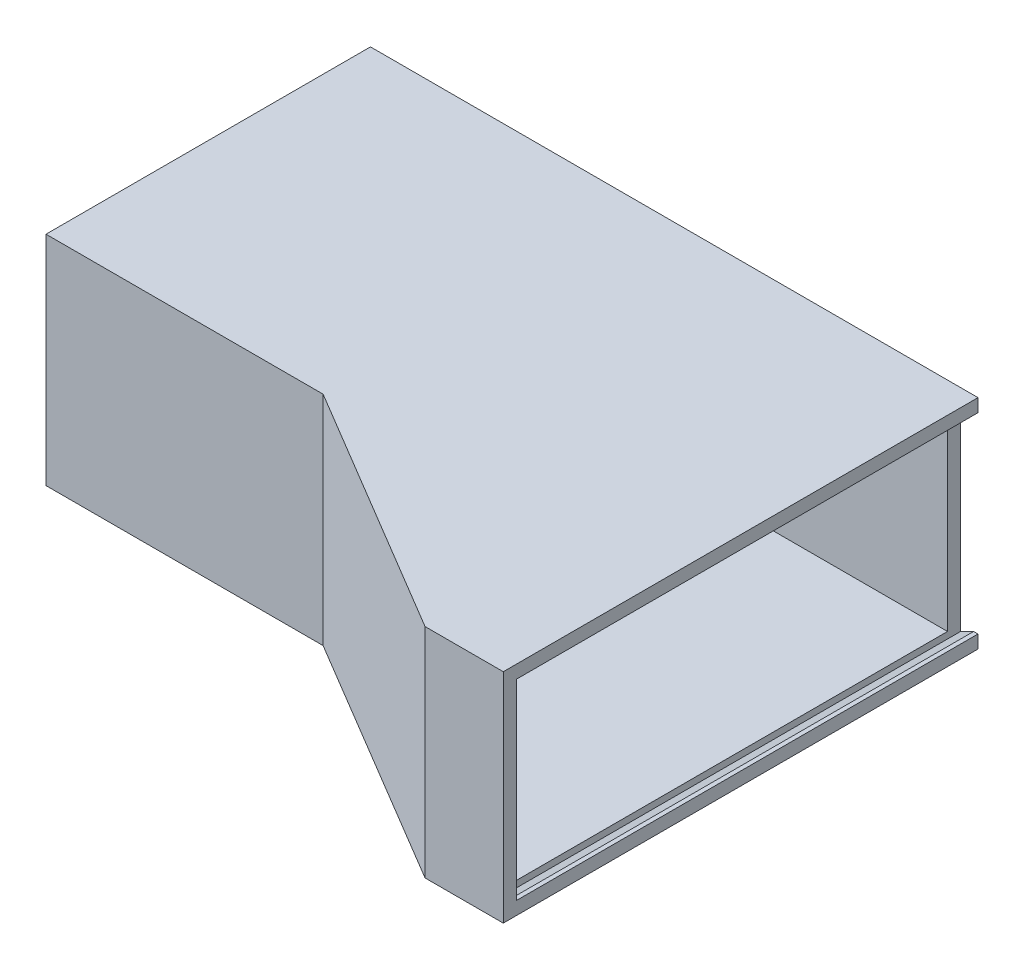
SolidWorks part; units mm, degrees
ref_plane "Front Plane" through (0, 0, 0) normal (0, 0, 1) x (1, 0, 0)
ref_plane "Top Plane" through (0, 0, 0) normal (0, 1, 0) x (1, 0, 0)
ref_plane "Right Plane" through (0, 0, 0) normal (1, 0, 0) x (0, 0, -1)
sketch "PCB" plane through (0, 0, 0) normal (0, 1, 0) x (1, 0, 0)
  line L0 (0, 0) -> (131.5, 0)
  line L1 (131.5, 0) -> (131.5, -102)
  line L2 (131.5, -102) -> (119, -102)
  line L3 (0, 0) -> (0, -67.5)
  line L4 (0, -67.5) -> (72, -67.5)
  line L5 (72, -67.5) -> (72, -74)
  line L6 (72, -74) -> (119, -102)
  line L7 (71.5, -74.2841) -> (118.8624, -102.5)
  line L8 (132, -102.5) -> (118.8624, -102.5)
  line L9 (132, 0.5) -> (132, -102.5)
  line L10 (-0.5, 0.5) -> (132, 0.5)
  line L11 (-0.5, 0.5) -> (-0.5, -68)
  line L12 (-0.5, -68) -> (71.5, -68)
  line L13 (71.5, -68) -> (71.5, -74.2841)
  line L14 (68.5, -75.9889) -> (118.0365, -105.5)
  line L15 (135, -105.5) -> (118.0365, -105.5)
  line L17 (-3.5, 3.5) -> (135, 3.5)
  line L18 (-3.5, 3.5) -> (-3.5, -71)
  line L19 (-3.5, -71) -> (60.1257, -71)
  line L21 (68.5, -75.9889) -> (60.1257, -71)
  line L22 (135, 3.5) -> (136, 3.5)
  line L24 (135, -105.5) -> (136, -105.5)
  line L25 (136, 3.5) -> (136, -105.5)
  line L26 (135, 3.5) -> (135, -105.5) construction
  line L27 (-3.5, -71) -> (68.5, -71) construction
  line L28 (68.5, -71) -> (68.5, -75.9889) construction
  line L29 (132, -102.5) -> (136, -102.5)
  line L30 (132, 0.5) -> (132, 3.5)
  dimension "D1" = 131.5
  dimension "D2" = 102
  dimension "D3" = 12.5
  dimension "D4" = 67.5
  dimension "D5" = 72
  dimension "D6" = 6.5
  dimension "D9" = 1
  dimension "D7" = 0.5
  dimension "D8" = 3
extrude "Boss-Extrude1" add sketch "PCB" along normal blind 25 contours L25 L22 L17 L18 L19 L21 L14 L15 L24 L13 L12 L11 L10 L9 L8 L7
sketch "Sketch4" plane through (0, 25, 0) normal (0, 1, 0) x (1, 0, 0)
  line L0 (118.0365, -105.5) -> (60.1257, -71)
  line L1 (-3.5, 3.5) -> (136, 3.5)
  line L2 (-3.5, 3.5) -> (-3.5, -71.0576)
  line L5 (136, -105.5) -> (118.0365, -105.5)
  line L6 (136, -105.5) -> (136, 3.5)
  line L7 (136, 3.5) -> (118.0365, 3.5)
  line L9 (-3.5, 3.5) -> (118.0365, 3.5)
  line L10 (-3.5, 3.5) -> (-3.5, -71.0576)
  line L11 (-3.5, -71.0576) -> (60.2224, -71.0576)
  line M10 (-0.5, 0.5) -> (132, 0.5)
  line M11 (132, 0.5) -> (132, 3.5)
  line M18 (136, -102.5) -> (118.8624, -102.5)
  line M19 (118.8624, -102.5) -> (71.5, -74.2841)
  line M20 (71.5, -74.2841) -> (71.5, -68)
  line M21 (71.5, -68) -> (-0.5, -68)
  line M22 (-0.5, -68) -> (-0.5, 0.5)
extrude "Boss-Extrude2" add sketch "Sketch4" against normal blind 3 contours L6 L1 M18 M11 M10 M22 M21 M20 M19
sketch "Sketch5" plane through (0, 0, 102.5) normal (0, 0, -1) x (-1, 0, 0)
  line L0 (-118.8624, 0) -> (-136, 0) construction
  line L1 (-135, 0) -> (-132, 0)
  line L2 (-135, 0) -> (-135, 22)
  line L3 (-135, 22) -> (-132, 22)
  line L4 (-132, 0) -> (-132, 22)
  line L5 (-136, 22) -> (-118.8624, 22) construction
  line L6 (-132, 22) -> (-132, 0) construction
  dimension "D1" = 3
extrude "Cut-Extrude1" cut sketch "Sketch5" against normal blind 1.5
sketch "Sketch6" plane through (0, 22, 0) normal (0, -1, 0) x (1, 0, 0)
  line L1 (132, -3.5) -> (135, -3.5)
  line L2 (132, -3.5) -> (132, 104)
  line L3 (132, 104) -> (135, 104)
  line L4 (135, -3.5) -> (135, 104)
extrude "Cut-Extrude2" cut sketch "Sketch6" against normal blind 1.5
sketch "Sketch7" plane through (0, 23.5, 0) normal (0, -1, 0) x (1, 0, 0)
  line L0 (135, 102.5) -> (132, 104)
  line L1 (132, 104) -> (135, 104)
  line L2 (135, 104) -> (135, 102.5)
extrude "Boss-Extrude4" add sketch "Sketch7" along normal blind 23.5
sketch "Sketch8" plane through (0, 0, 105.5) normal (0, 0, 1) x (1, 0, 0)
  line L0 (132, 23.5) -> (135, 23.5)
  line L3 (135, 23.5) -> (132, 23.5)
  line L5 (135, 23.5) -> (135, 22)
  line L6 (135, 22) -> (132, 23.5)
  line L7 (135, 23.5) -> (135, 25) construction
  line L8 (136, 25) -> (118.0365, 25) construction
  point P0 (0, 0)
  dimension "D1" = 1.5
  dimension "D3" = 3
  dimension "D4" = 1.5
extrude "Boss-Extrude5" add sketch "Sketch8" against normal blind 109 contours L6 L5 L0
mirror "Mirror2" about plane through (0, 0, 0) normal (0, 1, 0) of "Cut-Extrude1", "Cut-Extrude2", "Boss-Extrude1", "Boss-Extrude2", "Boss-Extrude5", "Boss-Extrude4"
